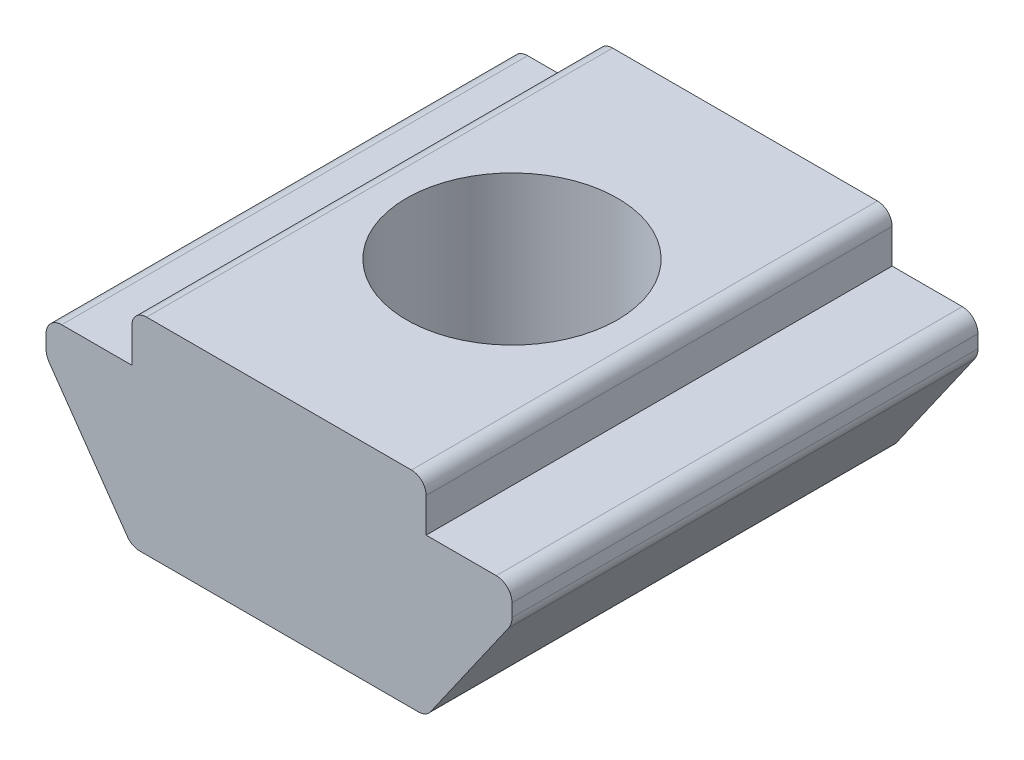
SolidWorks part; units mm, degrees
ref_plane "前视基准面" through (0, 0, 0) normal (0, 0, 1) x (1, 0, 0)
ref_plane "上视基准面" through (0, 0, 0) normal (0, 1, 0) x (1, 0, 0)
ref_plane "右视基准面" through (0, 0, 0) normal (1, 0, 0) x (0, 0, -1)
sketch "草图1" plane through (0, 0, 0) normal (0, 0, 1) x (1, 0, 0)
  line L0 (0, 19.2532) -> (0, -19.7565) construction
  line L1 (-3, 0) -> (3, 0)
  line L2 (3, 0) -> (3, -1)
  line L3 (3, -1) -> (4.75, -1)
  line L4 (4.75, -1) -> (4.75, -3.2517)
  line L5 (4.75, -3.2517) -> (3, -4.5)
  line L6 (3, -4.5) -> (-3, -4.5)
  line L7 (-4.75, -3.2517) -> (-3, -4.5)
  line L8 (-4.75, -1) -> (-4.75, -3.2517)
  line L9 (-3, -1) -> (-4.75, -1)
  line L10 (-3, 0) -> (-3, -1)
  dimension "D1" = 6
  dimension "D2" = 9.5
  dimension "D3" = 1
  dimension "D4" = 4.5
  dimension "D5" = 144.5
  dimension "D6" = 6
extrude "凸台-拉伸1" [suppressed] add sketch "草图1" along normal blind 10
sketch "草图2" [suppressed] plane through (0, 0, 0) normal (0, 1, 0) x (1, 0, 0)
  line L0 (0, 1.0228) -> (0, -10.3101) construction
  line L1 (-5.8897, -5) -> (5.8897, -5) construction
  line L2 (3, 0) -> (-3, 0) construction
  circle A0 centre (0, -5) radius 1.72
  dimension "D2" = 4.3
  dimension "D1" = 5
extrude "切除-拉伸1" [suppressed] cut sketch "草图2" against normal up to next
cosmetic thread "装饰螺纹线1" parameters "D2"=5
sketch "草图3" plane through (0, 0, 0) normal (0, 0, 1) x (1, 0, 0)
  line L0 (0, 26.8035) -> (0, -23.0283) construction
  line L1 (-2.7, 0) -> (2.7, 0)
  line L2 (3, -0.3) -> (3, -1)
  line L3 (3, -1) -> (4.43, -1)
  line L4 (4.75, -1.32) -> (4.75, -1.5825)
  line L5 (4.6822, -1.7976) -> (3.0896, -4.0721)
  line L6 (2.8438, -4.2) -> (-2.8438, -4.2)
  line L7 (-4.6822, -1.7976) -> (-3.0896, -4.0721)
  line L8 (-4.75, -1.32) -> (-4.75, -1.5825)
  line L9 (-3, -1) -> (-4.43, -1)
  line L10 (-3, -0.3) -> (-3, -1)
  arc A0 (4.75, -1.5825) -> (4.6822, -1.7976) centre (4.375, -1.5825) cw
  arc A1 (3.0896, -4.0721) -> (2.8438, -4.2) centre (2.8438, -3.9) cw
  arc A2 (4.43, -1) -> (4.75, -1.32) centre (4.43, -1.32) cw
  arc A3 (2.7, 0) -> (3, -0.3) centre (2.7, -0.3) cw
  arc A4 (-2.7, 0) -> (-3, -0.3) centre (-2.7, -0.3) ccw
  arc A5 (-4.43, -1) -> (-4.75, -1.32) centre (-4.43, -1.32) ccw
  arc A6 (-3.0896, -4.0721) -> (-2.8438, -4.2) centre (-2.8438, -3.9) ccw
  arc A7 (-4.75, -1.5825) -> (-4.6822, -1.7976) centre (-4.375, -1.5825) ccw
  point P14 (3, -4.2)
  point P19 (3, 0)
  point P33 (-3, 0)
  point P34 (-3, -4.2)
  dimension "D7" = 0.375
  dimension "D8" = 0.3
  dimension "D9" = 0.32
  dimension "D10" = 0.3
  dimension "D1" = 6
  dimension "D2" = 9.5
  dimension "D3" = 1
  dimension "D4" = 4.2
  dimension "D5" = 6
  dimension "D6" = 125
extrude "凸台-拉伸2" add sketch "草图3" along normal blind 9.5
sketch "草图4" plane through (0, 0, 0) normal (0, 1, 0) x (1, 0, 0)
  line L0 (0, 0) -> (0, -10.055) construction
  line L1 (-5.3369, -4.75) -> (5.4857, -4.75) construction
  line L2 (-3, 0) -> (-4.43, 0) construction
  circle A0 centre (0, -4.75) radius 2.15
  dimension "D2" = 4.3
  dimension "D1" = 4.75
extrude "切除-拉伸2" cut sketch "草图4" against normal up to next
cosmetic thread "装饰螺纹线2" parameters "D2"=5
